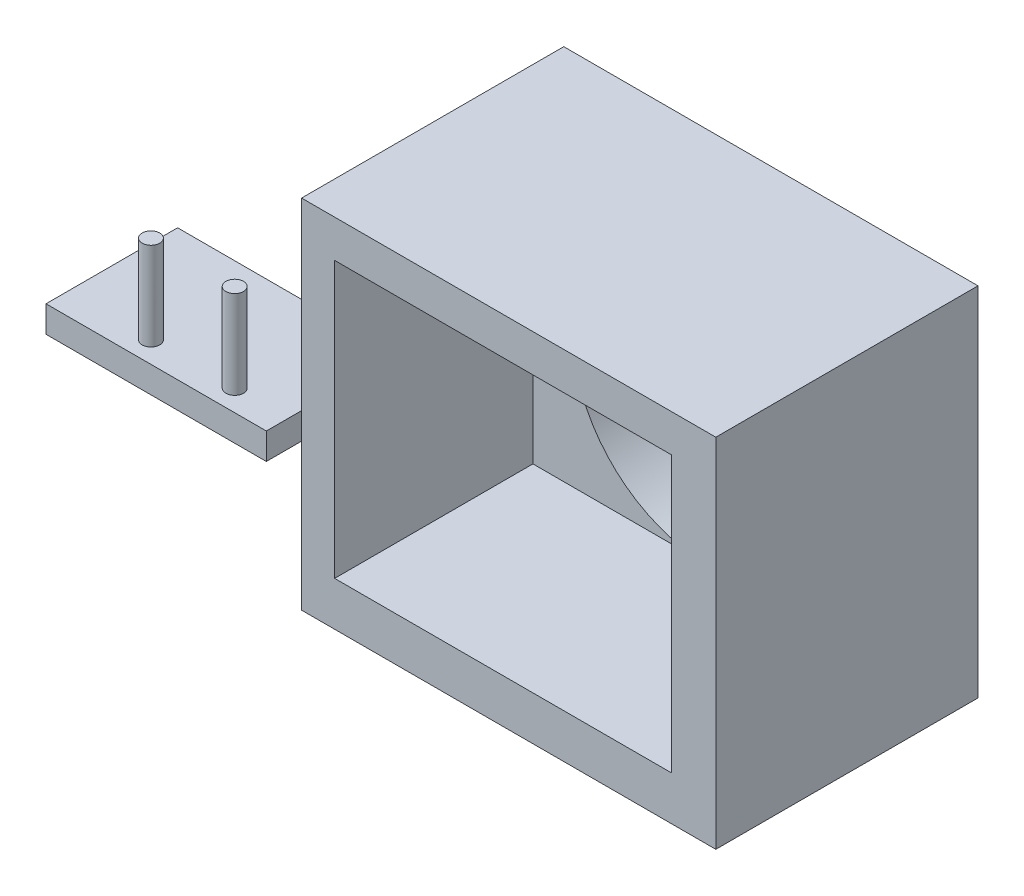
SolidWorks part; units mm, degrees
ref_plane "Alzado" through (0, 0, 0) normal (0, 0, 1) x (1, 0, 0)
ref_plane "Planta" through (0, 0, 0) normal (0, 1, 0) x (1, 0, 0)
ref_plane "Vista lateral" through (0, 0, 0) normal (1, 0, 0) x (0, 0, -1)
ref_plane "Plano1" through (0, 0, 25) normal (0, 0, 1) x (1, 0, 0)
sketch "Croquis1" plane through (0, 0, 25) normal (0, 0, 1) x (1, 0, 0)
  line L0 (-45.7431, 54.4363) -> (-45.7431, 13.9363)
  line L1 (-45.7431, 13.9363) -> (1.2569, 13.9363)
  line L2 (1.2569, 13.9363) -> (1.2569, 54.4363)
  line L3 (1.2569, 54.4363) -> (-45.7431, 54.4363)
extrude "Saliente-Extruir1" add sketch "Croquis1" against normal blind 25
sketch "Croquis2" plane through (-45.7431, 0, 0) normal (-1, 0, 0) x (0, 0, 1)
  line L0 (25, 30.5463) -> (14.0661, 30.5463)
  line L1 (14.0661, 30.5463) -> (14.0661, 33.5463)
  line L2 (14.0661, 33.5463) -> (25, 33.5463)
  line L3 (25, 33.5463) -> (25, 30.5463)
extrude "Saliente-Extruir2" add sketch "Croquis2" along normal blind 25
sketch "Croquis3" plane through (0, 0, 25) normal (0, 0, 1) x (1, 0, 0)
  line L0 (-3.7431, 50.1863) -> (-41.9931, 50.1863)
  line L1 (-41.9931, 50.1863) -> (-41.9931, 18.9363)
  line L2 (-41.9931, 18.9363) -> (-3.7431, 18.9363)
  line L3 (-3.7431, 18.9363) -> (-3.7431, 50.1863)
  dimension "D1" = 31.25
  dimension "D2" = 38.25
extrude "Cortar-Extruir1" cut sketch "Croquis3" against normal blind 22.5
sketch "Croquis6" plane through (0, 0, 0) normal (0, 0, -1) x (-1, 0, 0)
  circle A0 centre (22.2431, 34.1863) radius 15.25
  dimension "D1" = 30.5
extrude "Cortar-Extruir2" cut sketch "Croquis6" against normal blind 10
sketch "Croquis7" plane through (0, 0, 0) normal (0, 0, -1) x (-1, 0, 0)
  line L0 (-1.2569, 54.4363) -> (45.7431, 54.4363)
  line L1 (-1.2569, 54.4363) -> (-1.2569, 13.9363)
  line L2 (45.7431, 54.4363) -> (45.7431, 13.9363)
  line L3 (-1.2569, 13.9363) -> (45.7431, 13.9363)
  circle A0 centre (22.2431, 34.1863) radius 15.25
  dimension "D1" = 40.5
extrude "Saliente-Extruir5" add sketch "Croquis7" along normal blind 4.75
sketch "Croquis8" plane through (0, 33.5463, 0) normal (0, 1, 0) x (1, 0, 0)
  line L0 (-70.7431, -25) -> (-70.7431, -29)
  line L1 (-45.7431, -25) -> (-45.7431, -29)
  line L2 (-45.7431, -29) -> (-70.7431, -29)
  line L3 (-70.7431, -25) -> (-45.7431, -25)
  dimension "D1" = 4
extrude "Saliente-Extruir6" add sketch "Croquis8" against normal blind 3
sketch "Croquis9" plane through (0, 33.5463, 0) normal (0, 1, 0) x (1, 0, 0)
  circle A0 centre (-61.2431, -26.5904) radius 1
  circle A1 centre (-51.7431, -26.5904) radius 1
  dimension "D5" = 2
  dimension "D6" = 2
extrude "Saliente-Extruir7" add sketch "Croquis9" along normal blind 10
